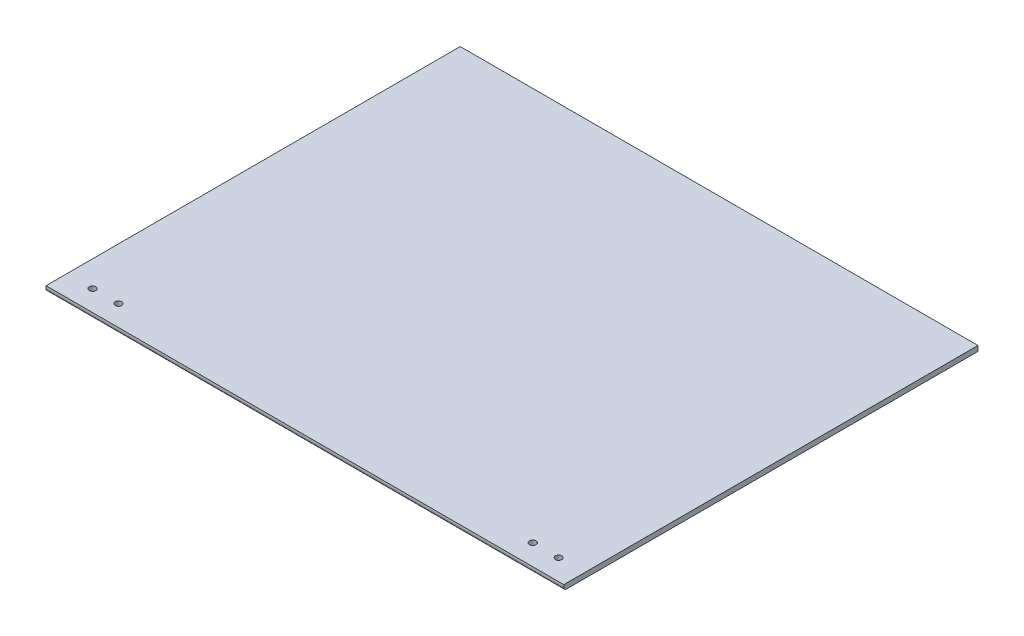
SolidWorks part; units mm, degrees
ref_plane "Front Plane" through (0, 0, 0) normal (0, 0, 1) x (1, 0, 0)
ref_plane "Top Plane" through (0, 0, 0) normal (0, 1, 0) x (1, 0, 0)
ref_plane "Right Plane" through (0, 0, 0) normal (1, 0, 0) x (0, 0, -1)
sketch "Sketch1" plane through (0, 0, 0) normal (0, 1, 0) x (1, 0, 0)
  line L1 (0, 0) -> (500, 0)
  line L2 (0, 0) -> (0, 400)
  line L3 (0, 400) -> (500, 400)
  line L4 (500, 0) -> (500, 400)
  dimension "D1" = 400
  dimension "D2" = 500
extrude "Boss-Extrude1" add sketch "Sketch1" along normal blind 5
ref_plane "Plane1" through (500, 5, 0) normal (0, 0, -1) x (-1, 0, 0)
sketch "Sketch3" plane through (0, 5, 0) normal (0, 1, 0) x (1, 0, 0)
  line L0 (0, 0) -> (500, 0) construction
  line L1 (500, 0) -> (500, 400) construction
  line L2 (250, 0) -> (250, 400)
  line L3 (500, 400) -> (0, 400) construction
  circle A0 centre (475, 20) radius 3.175
  circle A1 centre (450, 20) radius 3.175
  circle A2 centre (25, 20) radius 3.175
  circle A3 centre (50, 20) radius 3.175
  dimension "D2" = 6.35
  dimension "D3" = 6.35
  dimension "D1" = 20
  dimension "D4" = 25
  dimension "D5" = 25
extrude "Cut-Extrude1" cut sketch "Sketch3" against normal blind 10 contours A2 | A3 | A0 | A1
fillet "Fillet1" radius 2.5 1 edges at (250, 0, 0)
